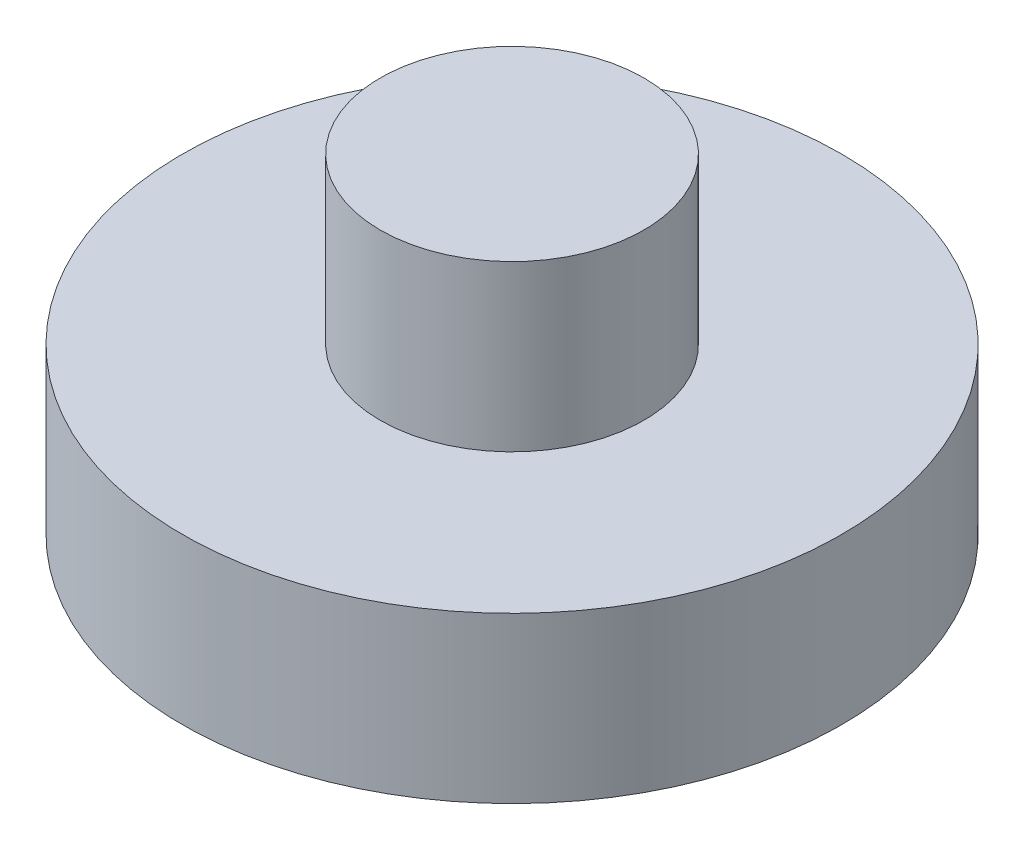
SolidWorks part; units mm, degrees
ref_plane "Front Plane" through (0, 0, 0) normal (0, 0, 1) x (1, 0, 0)
ref_plane "Top Plane" through (0, 0, 0) normal (0, 1, 0) x (1, 0, 0)
ref_plane "Right Plane" through (0, 0, 0) normal (1, 0, 0) x (0, 0, -1)
sketch "Sketch1" plane through (0, 0, 0) normal (0, 0, 1) x (1, 0, 0)
  line L0 (0, 0) -> (0, 12.7)
  line L1 (0, 12.7) -> (5.08, 12.7)
  line L2 (5.08, 12.7) -> (5.08, 6.35)
  line L3 (5.08, 6.35) -> (12.7, 6.35)
  line L4 (12.7, 6.35) -> (12.7, 0)
  line L5 (12.7, 0) -> (0, 0)
  dimension "D1" = 5.08
  dimension "D2" = 12.7
  dimension "D3" = 6.35
  dimension "D4" = 12.7
revolve "Revolve1" add sketch "Sketch1" angle 360 about L0
